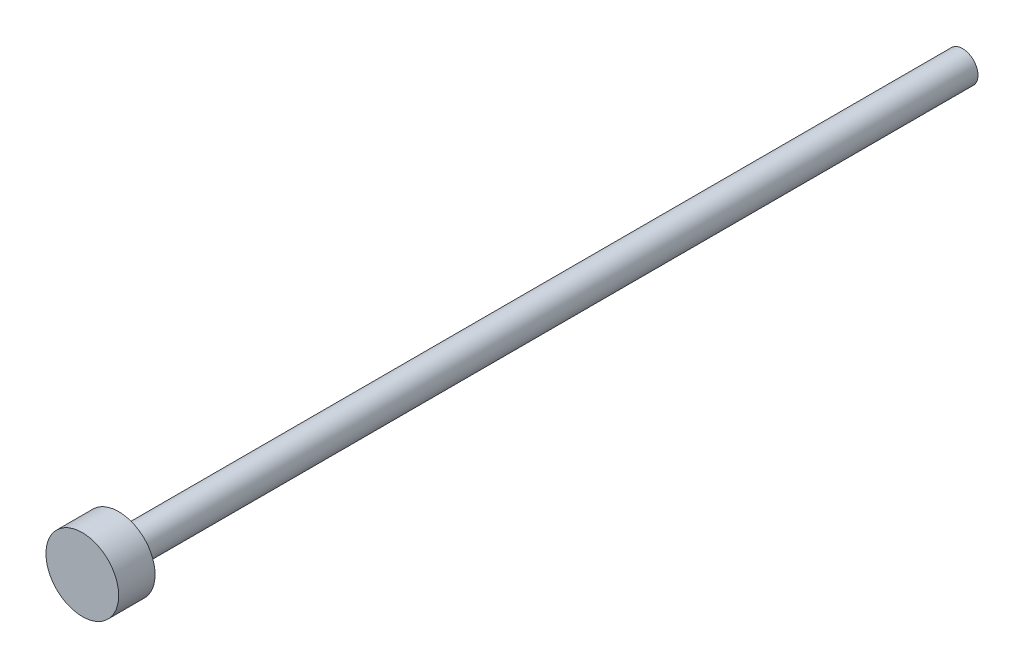
SolidWorks part; units mm, degrees
other "细节项目1"
other "细节项目2"
ref_plane "前视基准面" through (0, 0, 0) normal (0, 0, 1) x (1, 0, 0)
ref_plane "上视基准面" through (0, 0, 0) normal (0, 1, 0) x (1, 0, 0)
ref_plane "右视基准面" through (0, 0, 0) normal (1, 0, 0) x (0, 0, -1)
sketch "草图2" plane through (0, 0, 0) normal (0, 0, 1) x (1, 0, 0)
  circle A1 centre (3.25, -1.5) radius 0.425
  circle A2 centre (3.25, -1.5) radius 0.68 construction
  circle A3 centre (3.25, -1.5) radius 0.68
  dimension "D2" = 0.85
extrude "凸台-拉伸1" add sketch "草图2" against normal blind 23.2 and the other way blind 1 contours A1
sketch "草图4" plane through (0, 0, 1) normal (0, 0, 1) x (1, 0, 0)
  circle A1 centre (3.25, -1.5) radius 0.425 construction
  circle A2 centre (3.25, -1.5) radius 0.425
  circle A3 centre (3.25, -1.5) radius 1
  circle M3 centre (3.25, -1.5) radius 0.425
  dimension "D1" = 2
extrude "凸台-拉伸2" add sketch "草图4" against normal up to surface (1 mm away) contours A3 M3 | M3
sketch "草图5" plane through (0, 0, -23.2) normal (0, 0, -1) x (-1, 0, 0)
  circle A0 centre (-3.25, -1.5) radius 0.425 construction
  circle A1 centre (-3.25, -1.5) radius 0.425
  circle A2 centre (-3.25, -1.5) radius 0.5
  circle A3 centre (-3.25, -1.5) radius 1 construction
  dimension "D1" = 1
